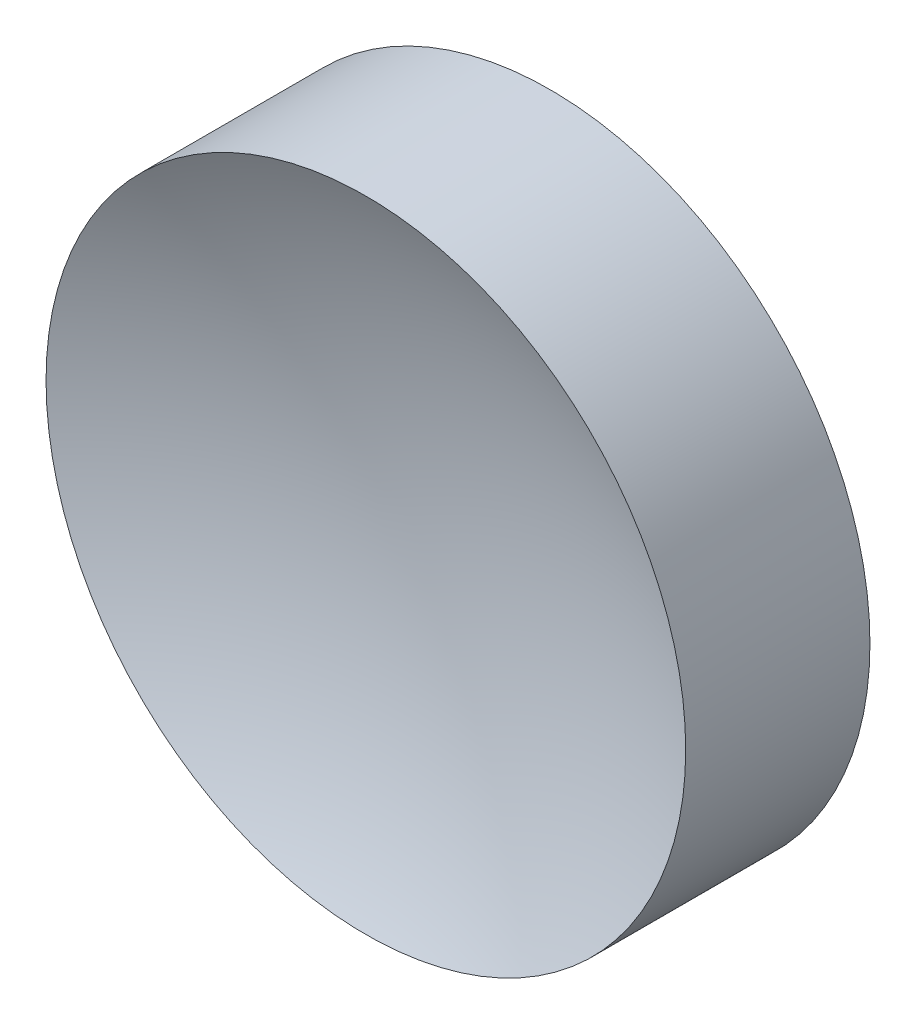
SolidWorks part; units mm, degrees
ref_plane "前视基准面" through (0, 0, 0) normal (0, 0, 1) x (1, 0, 0)
ref_plane "上视基准面" through (0, 0, 0) normal (0, 1, 0) x (1, 0, 0)
ref_plane "右视基准面" through (0, 0, 0) normal (1, 0, 0) x (0, 0, -1)
other "Configuration Table"
sketch "草图1" plane through (0, 0, 0) normal (0, 1, 0) x (1, 0, 0)
  line L0 (0, 0) -> (0, 1.4)
  line L1 (0, 0.7) -> (-12, 0.7) construction
  line L2 (-12, 4.1563) -> (-12, -2.7563)
  arc A0 (0, 0) -> (-12, -2.7563) centre (0, -27.5) ccw
  arc A1 (0, 1.4) -> (-12, 4.1563) centre (0, 28.9) cw
  dimension "D2" = 55
  dimension "D1" = 1.4
  dimension "D3" = 12
revolve "旋转1" add sketch "草图1" angle 360 about L0
